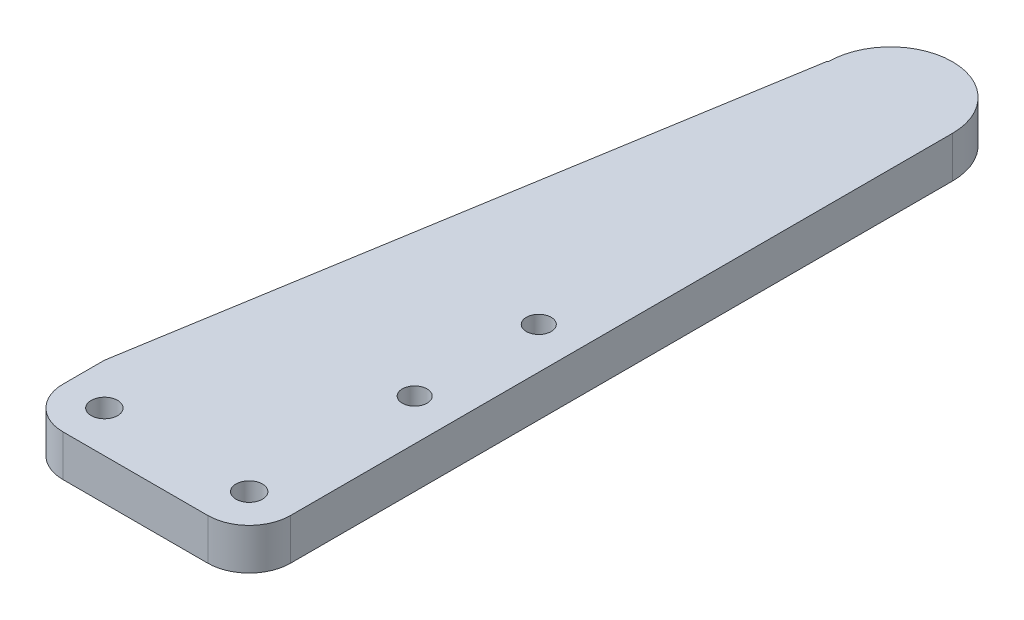
SolidWorks part; units mm, degrees
material "ﾎﾟﾘ塩化ﾋﾞﾆﾙ(PVC)硬質"
ref_plane "正面" through (0, 0, 0) normal (0, 0, 1) x (1, 0, 0)
ref_plane "平面" through (0, 0, 0) normal (0, 1, 0) x (1, 0, 0)
ref_plane "右側面" through (0, 0, 0) normal (1, 0, 0) x (0, 0, -1)
sketch "ｽｹｯﾁ1" plane through (0, 0, 0) normal (0, 1, 0) x (1, 0, 0)
  line L0 (-13.75, -37.5) -> (13.75, -37.5) construction
  line L1 (-13.75, -42.5) -> (13.75, -42.5)
  line L2 (-13.75, -42.5) -> (-13.75, 42.5)
  line L3 (-13.75, 42.5) -> (13.75, 42.5)
  line L4 (13.75, -42.5) -> (13.75, 42.5)
  line L5 (-13.75, -42.5) -> (13.75, 42.5) construction
  line L6 (-13.75, 42.5) -> (13.75, -42.5) construction
  line L7 (0, 42.5) -> (0, -42.5) construction
  line L8 (-13.75, 0) -> (13.75, 0) construction
  line L9 (-1.1496, 43.7232) -> (-13.75, -32.5)
  line L10 (8.75, -17.5) -> (8.75, -2.5) construction
  circle A0 centre (-8.75, -37.5) radius 1.6
  circle A1 centre (8.75, -37.5) radius 1.6
  circle A2 centre (6.25, 42.5) radius 7.5
  circle A3 centre (8.75, -17.5) radius 1.5
  circle A4 centre (8.75, -2.5) radius 1.5
  point P0 (0, 0)
  dimension "D1" = 5
  dimension "D2" = 5
  dimension "D3" = 17.5
  dimension "D5" = 15
  dimension "D6" = 80
  dimension "D7" = 3.2
  dimension "D9" = 5
  dimension "D10" = 3
  dimension "D11" = 25
  dimension "D4" = 5
  dimension "D8" = 15
extrude "ﾎﾞｽ - 押し出し1" add sketch "ｽｹｯﾁ1" along normal blind 5 contours L3 A2 | L3 A2 | A2 L3 L9 L2 L1 L4 A0 A1
fillet "ﾌｨﾚｯﾄ1" radius 5 2 edges at (-13.75, 2.5, 42.5) (13.75, 2.5, 42.5)
